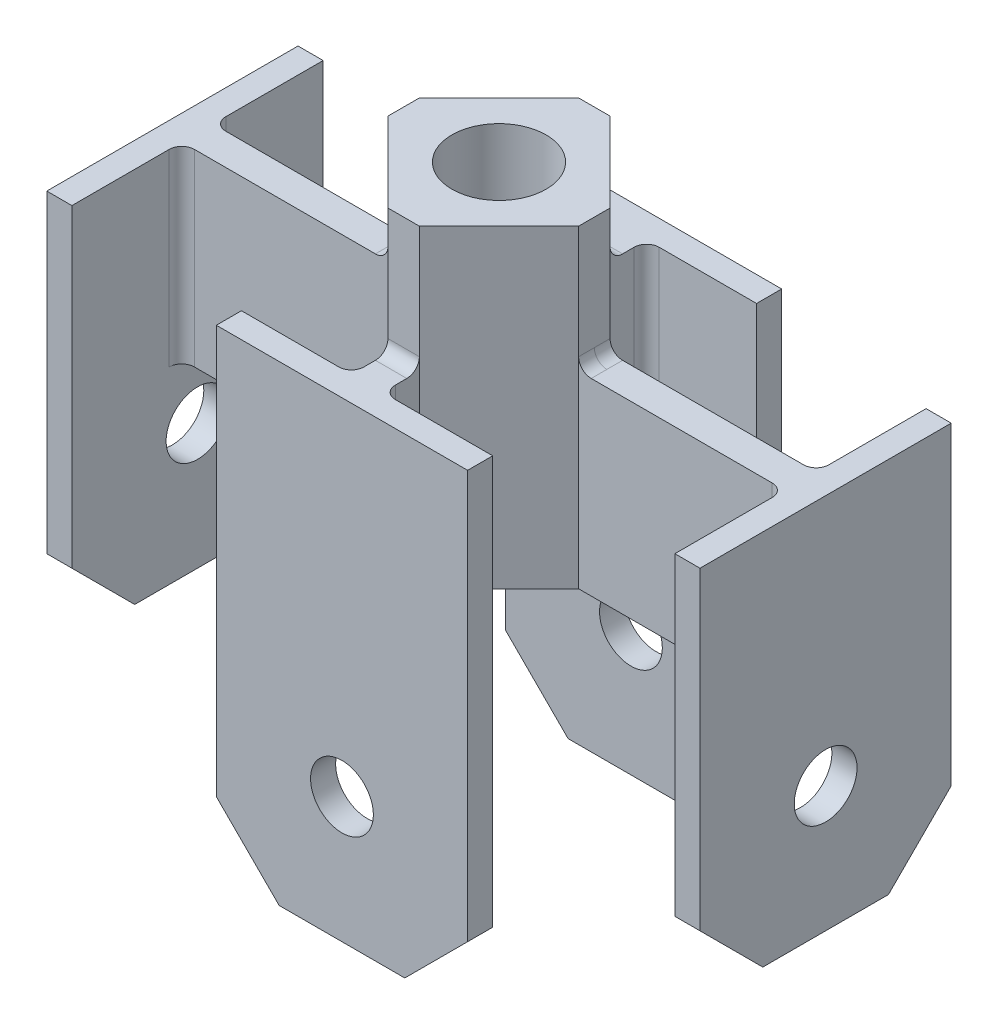
SolidWorks part; units mm, degrees
ref_plane "Front Plane" through (0, 0, 0) normal (0, 0, 1) x (1, 0, 0)
ref_plane "Top Plane" through (0, 0, 0) normal (0, 1, 0) x (1, 0, 0)
ref_plane "Right Plane" through (0, 0, 0) normal (1, 0, 0) x (0, 0, -1)
sketch "Sketch1" plane through (0, 0, 0) normal (0, 1, 0) x (1, 0, 0)
  line L0 (0, 0) -> (0, 25.4)
  line L1 (0, 0) -> (43.5864, 0)
  line L2 (0, 25.4) -> (5.08, 25.4)
  line L3 (5.08, 25.4) -> (5.08, 5.715)
  line L4 (7.62, 3.175) -> (43.5864, 3.175)
  line L5 (43.5864, 3.175) -> (43.5864, 0)
  line L6 (5.08, 3.175) -> (5.08, 0)
  line L13 (43.5864, 3.175) -> (46.7614, 3.175)
  line L14 (43.5864, 3.175) -> (43.5864, 0)
  line L15 (43.5864, 0) -> (46.7614, 0)
  line L16 (46.7614, 3.175) -> (46.7614, 0)
  line L20 (66.037, 22.4506) -> (62.862, 22.4506)
  line L23 (43.5864, 0) -> (66.037, 0)
  line L24 (66.037, 31.75) -> (40.637, 31.75)
  line L25 (40.637, 31.75) -> (40.637, 26.67)
  line L26 (40.637, 26.67) -> (60.322, 26.67)
  line L27 (62.862, 24.13) -> (62.862, 22.4506)
  line L28 (66.037, 31.75) -> (66.037, 22.4506)
  line L29 (66.037, 0) -> (66.037, 22.4506)
  line L31 (46.7614, 3.175) -> (46.7614, 0)
  line L33 (66.037, 22.4506) -> (43.5864, 0)
  line L34 (60.322, 26.67) -> (66.037, 26.67)
  line L35 (62.862, 22.4506) -> (66.037, 22.4506)
  line L36 (62.862, 22.4506) -> (62.862, 19.2756)
  line L37 (62.862, 19.2756) -> (66.037, 19.2756)
  line L38 (66.037, 22.4506) -> (66.037, 19.2756)
  arc A0 (60.322, 26.67) -> (62.862, 24.13) centre (60.322, 24.13) cw
  arc A1 (5.08, 5.715) -> (7.62, 3.175) centre (7.62, 5.715) ccw
  point P15 (0, 0)
  point P17 (0, 0)
  dimension "D9" = 2.54
  dimension "D6" = 2.54
  dimension "D1" = 3.175
  dimension "D2" = 25.4
  dimension "D3" = 5.08
  dimension "D4" = 45
  dimension "D5" = 38.5064
  dimension "D7" = 31.75
  dimension "D8" = 22.4506
  dimension "D10" = 3.175
  dimension "D11" = 5.08
  dimension "D12" = 25.4
extrude "Boss-Extrude2" add sketch "Sketch1" along normal blind 25.4 and the other way blind 38.1 contours L37 L33 L16 L23 L29
sketch "Sketch2" plane through (0, 0, 0) normal (0, 1, 0) x (1, 0, 0)
  line L0 (0, 0) -> (46.7614, 0) construction
  line L1 (0, 0) -> (0, 34.3049) construction
  line L2 (0, 34.3049) -> (5.08, 34.3049) construction
  line L3 (5.08, 34.3049) -> (5.08, 3.175) construction
  line L4 (5.08, 3.175) -> (46.7614, 3.175) construction
  line L6 (5.08, 0) -> (46.7614, 0)
  line L7 (5.08, 0) -> (5.08, 3.175)
  line L8 (5.08, 3.175) -> (46.7614, 3.175)
  line L9 (46.7614, 0) -> (46.7614, 3.175)
  dimension "D1" = 41.6814
extrude "Boss-Extrude3" add sketch "Sketch2" against normal blind 38.1
sketch "Sketch3" plane through (0, 0, 0) normal (0, 1, 0) x (1, 0, 0)
  line L0 (0, 0) -> (5.08, 0)
  line L1 (0, 0) -> (0, 25.4)
  line L2 (5.08, 0) -> (5.08, 25.4)
  line L3 (0, 25.4) -> (5.08, 25.4)
  dimension "D1" = 25.4
extrude "Boss-Extrude4" add sketch "Sketch3" against normal blind 76.2
sketch "Sketch4" plane through (0, 0, 0) normal (0, 1, 0) x (1, 0, 0)
  line L0 (62.862, 19.2756) -> (66.037, 19.2756)
  line L1 (62.862, 19.2756) -> (62.862, 26.6742)
  line L2 (66.037, 19.2756) -> (66.037, 26.6742)
  line L3 (62.862, 26.6742) -> (66.037, 26.6742)
extrude "Boss-Extrude5" add sketch "Sketch4" against normal blind 38.1
sketch "Sketch5" plane through (0, 0, 0) normal (0, 1, 0) x (1, 0, 0)
  line L1 (66.037, 26.6742) -> (40.637, 26.6742)
  line L2 (66.037, 26.6742) -> (66.037, 31.75)
  line L3 (66.037, 31.75) -> (40.637, 31.75)
  line L4 (40.637, 26.6742) -> (40.637, 31.75)
extrude "Boss-Extrude6" add sketch "Sketch5" against normal blind 95.25
fillet "Fillet1" radius 2.54 3 edges at (5.08, -19.05, -3.175) (46.7614, 0, -1.5875) (62.862, -19.05, -26.6742)
sketch "Sketch7" plane through (0, 0, -31.75) normal (0, 0, -1) x (-1, 0, 0)
  line L0 (-40.637, -82.55) -> (-53.337, -95.25)
  line L1 (-53.337, -95.25) -> (-40.637, -95.25)
  line L2 (-40.637, -95.25) -> (-40.637, -82.55)
  line L3 (-40.637, -95.25) -> (-40.637, 0) construction
  point P0 (-58.567, -95.25)
  dimension "D1" = 12.7
  dimension "D2" = 12.7
extrude "Cut-Extrude1" cut sketch "Sketch7" against normal up to surface (5.0758 mm away) up to face at (55.6654, -44.45, -26.6742)
sketch "Sketch8" plane through (0, 0, 0) normal (-1, 0, 0) x (0, 0, 1)
  line L0 (-25.4, -76.2) -> (-25.4, -63.5)
  line L1 (-25.4, -76.2) -> (-25.4, 0) construction
  line L2 (-25.4, -63.5) -> (-12.7, -76.2)
  line L3 (-25.4, -76.2) -> (0, -76.2) construction
  line L4 (-12.7, -76.2) -> (-25.4, -76.2)
  dimension "D1" = 12.7
extrude "Cut-Extrude2" cut sketch "Sketch8" against normal up to surface (5.08 mm away) up to face at (5.08, -38.1, -10.3717)
mirror "Mirror5" about plane through (0, -38.1, 0) normal (0, 0, 1) of "Cut-Extrude2", "Cut-Extrude1", "Fillet1", "Boss-Extrude6", "Boss-Extrude5", "Boss-Extrude4", "Boss-Extrude3", "Boss-Extrude2"
mirror "Mirror6" about plane through (66.037, -38.1, 0) normal (1, 0, 0) of bodies 110
fillet "Fillet3" radius 2.54 2 edges at (66.037, 0, 19.2756) (66.037, 0, -19.2756)
sketch "Sketch9" plane through (0, 25.4, 0) normal (0, 1, 0) x (1, 0, 0)
  circle A0 centre (66.037, 0) radius 9.525
  dimension "D1" = 19.05
extrude "Cut-Extrude3" cut sketch "Sketch9" against normal blind 50.8
sketch "Sketch11" plane through (132.0741, 0, 0) normal (1, 0, 0) x (0, 0, -1)
  line L0 (0, 0) -> (0, -105.0559) construction
  line L1 (12.7, -76.2) -> (-12.7, -76.2) construction
  circle A0 centre (0, -50.8) radius 6.35
  dimension "D1" = 12.7
  dimension "D2" = 25.4
extrude "Cut-Extrude4" cut sketch "Sketch11" against normal through all
sketch "Sketch12" plane through (0, 0, 31.75) normal (0, 0, 1) x (1, 0, 0)
  line L0 (66.037, -7.916) -> (66.037, -109.7833) construction
  line L1 (78.737, -95.25) -> (53.337, -95.25) construction
  circle A0 centre (66.037, -69.85) radius 6.35
  point P4 (0, 0)
  dimension "D1" = 12.7
  dimension "D2" = 25.4
extrude "Cut-Extrude5" cut sketch "Sketch12" against normal through all
